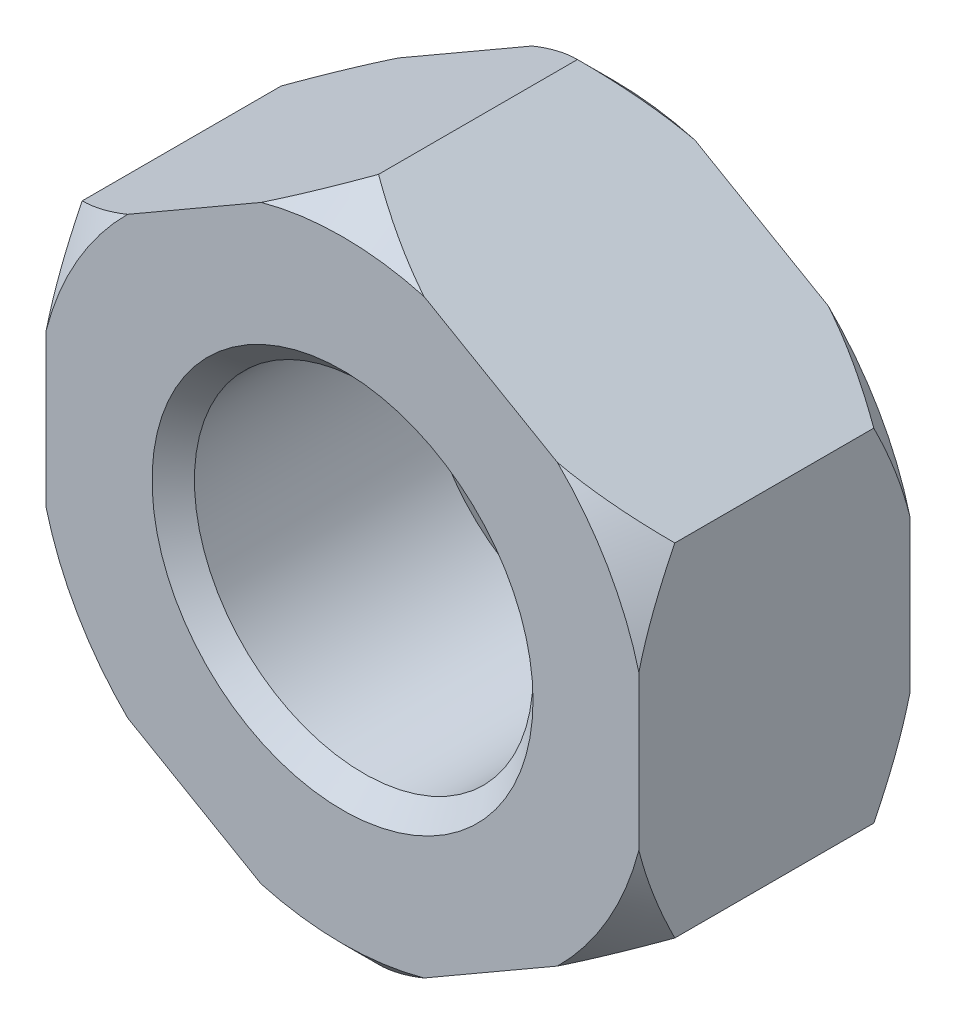
SolidWorks part; units mm, degrees
ref_plane "Спереди" through (0, 0, 0) normal (0, 0, 1) x (1, 0, 0)
ref_plane "Сверху" through (0, 0, 0) normal (0, 1, 0) x (1, 0, 0)
ref_plane "Справа" through (0, 0, 0) normal (1, 0, 0) x (0, 0, -1)
sketch "Эскиз1" plane through (0, 0, 0) normal (0, 0, 1) x (1, 0, 0)
  line L0 (0, 3.7738) -> (0, -4.1898) construction
  line L1 (-3.4469, 0) -> (3.2389, 0) construction
  line L3 (0, 4.0415) -> (-3.5, 2.0207)
  line L4 (-3.5, 2.0207) -> (-3.5, -2.0207)
  line L5 (-3.5, -2.0207) -> (0, -4.0415)
  line L6 (0, -4.0415) -> (3.5, -2.0207)
  line L7 (3.5, -2.0207) -> (3.5, 2.0207)
  line L8 (3.5, 2.0207) -> (0, 4.0415)
  circle A0 centre (0, 0) radius 3.5 construction
extrude "Вытянуть1" add sketch "Эскиз1" along normal blind 3.2
sketch "Эскиз2" plane through (0, 0, 0) normal (0, 0, -1) x (-1, 0, 0)
  circle A0 centre (0, 0) radius 2
ref_axis "Ось4" through (0, 0, 2.6338) along (0, 0, -1)
sketch "Эскиз15" plane through (0, 0, 0) normal (1, 0, 0) x (0, 0, -1)
  line L0 (-3.2, 4.0415) -> (-3.2, 3.6165)
  line L1 (-3.2, 2.0207) -> (-3.2, 4.0415) construction
  line L2 (-3.2, 3.6165) -> (-2.775, 4.0415)
  line L3 (-3.2, 4.0415) -> (0, 4.0415) construction
  line L4 (-2.775, 4.0415) -> (-3.2, 4.0415)
  line L5 (-0.425, 4.0415) -> (0, 4.0415)
  line L6 (0, 4.0415) -> (0, 3.6165)
  line L7 (0, 3.6165) -> (-0.425, 4.0415)
revolve "Вырез-Повернуть1" cut sketch "Эскиз15" angle 360 about axis through (0, 0, 2.6338) along (0, 0, -1)
ref_plane "Плоскость1" through (3.5, 0.9103, 3.2) normal (-0.2517, 0.9678, 0) x (-0.9678, -0.2517, 0)
extrude "Вырез-Вытянуть1" cut sketch "Эскиз2" against normal through all
chamfer "Фаска1" distance 0.25 angle 45 2 edges at (-2, 0, 0) (-2, 0, 3.2)
